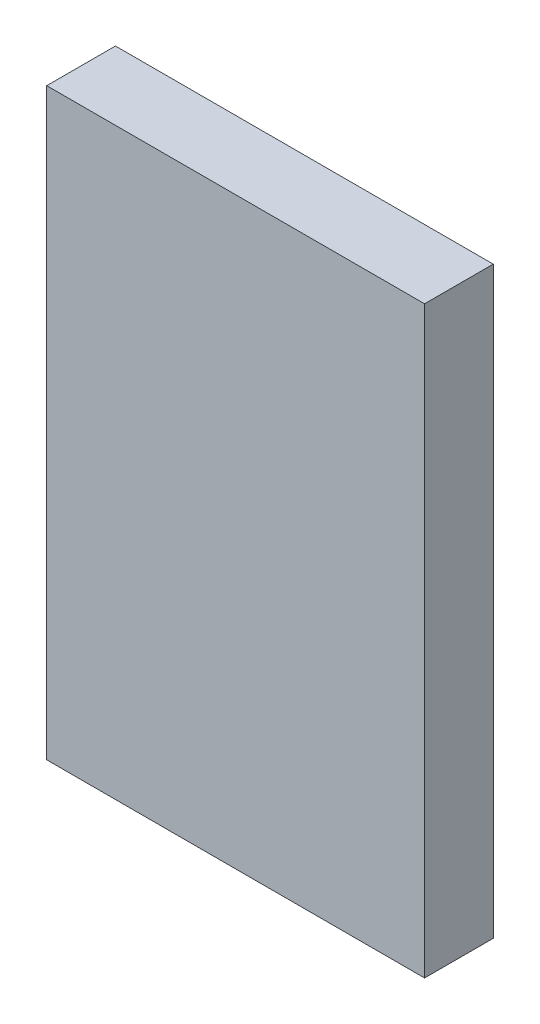
SolidWorks part; units mm, degrees
ref_plane "Plan de face" through (0, 0, 0) normal (0, 0, 1) x (1, 0, 0)
ref_plane "Plan de dessus" through (0, 0, 0) normal (0, 1, 0) x (1, 0, 0)
ref_plane "Plan de droite" through (0, 0, 0) normal (1, 0, 0) x (0, 0, -1)
sketch "Esquisse1" plane through (0, 0, 0) normal (0, 0, 1) x (1, 0, 0)
  line L1 (-27.5, 42.5) -> (27.5, 42.5)
  line L2 (-27.5, 42.5) -> (-27.5, -42.5)
  line L3 (-27.5, -42.5) -> (27.5, -42.5)
  line L4 (27.5, 42.5) -> (27.5, -42.5)
  point P4 (-27.5, 0)
  point P6 (0, 42.5)
  dimension "D1" = 55
  dimension "D2" = 85
extrude "Boss.-Extru.1" add sketch "Esquisse1" along normal blind 10
